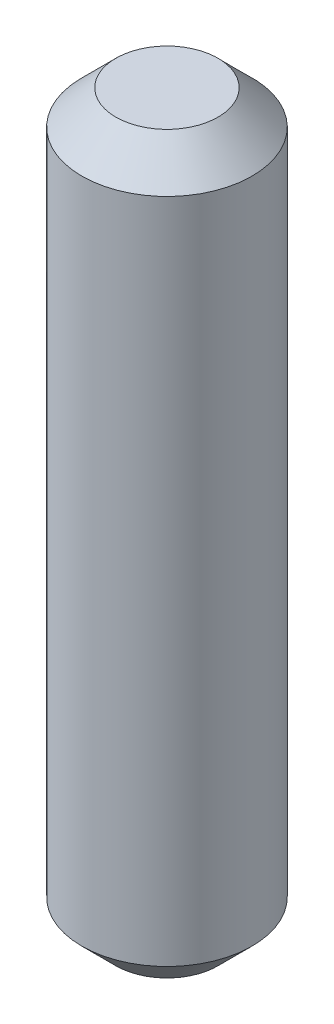
SolidWorks part; units mm, degrees
ref_plane "Front Plane" through (0, 0, 0) normal (0, 0, 1) x (1, 0, 0)
ref_plane "Top Plane" through (0, 0, 0) normal (0, 1, 0) x (1, 0, 0)
ref_plane "Right Plane" through (0, 0, 0) normal (1, 0, 0) x (0, 0, -1)
sketch "Sketch1" plane through (0, 0, 0) normal (0, 1, 0) x (1, 0, 0)
  circle A0 centre (0, 0) radius 2.5
  dimension "D1" = 5
extrude "Boss-Extrude1" add sketch "Sketch1" along normal blind 21.59
chamfer "Chamfer1" distance 1 2 edges at (0, 0, 2.5) (0, 21.59, 2.5)
